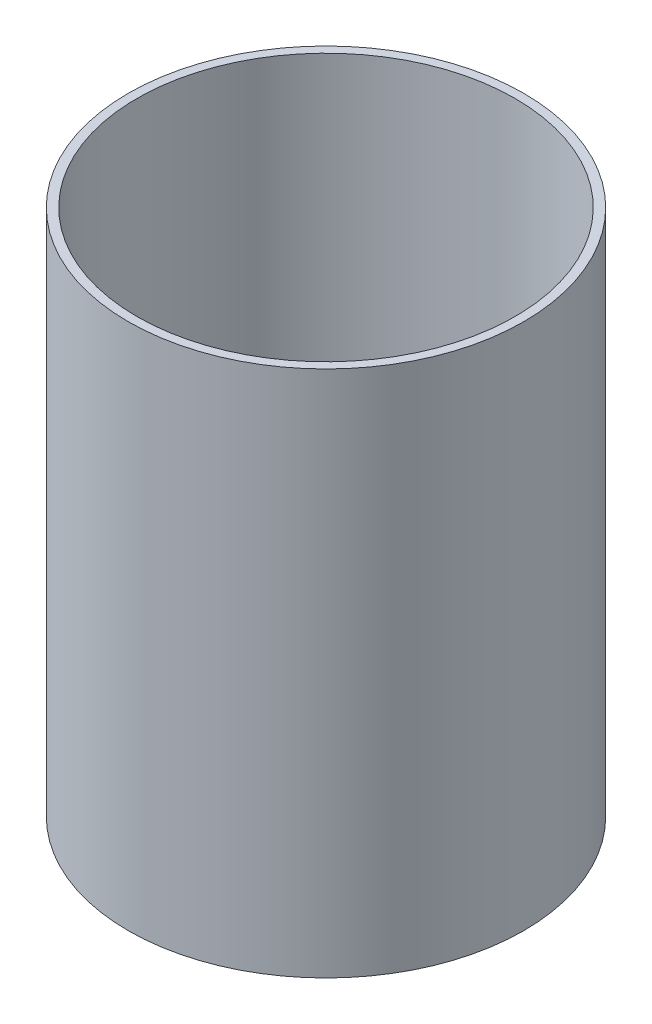
SolidWorks part; units mm, degrees
material "PET"
ref_plane "Front Plane" through (0, 0, 0) normal (0, 0, 1) x (1, 0, 0)
ref_plane "Top Plane" through (0, 0, 0) normal (0, 1, 0) x (1, 0, 0)
ref_plane "Right Plane" through (0, 0, 0) normal (1, 0, 0) x (0, 0, -1)
other "Configuration Table"
sketch "Sketch1" plane through (0, 0, 0) normal (0, 1, 0) x (1, 0, 0)
  circle A0 centre (0, 0) radius 45
  dimension "D1" = 90
extrude "Jar_Body" add sketch "Sketch1" along normal blind 120
sketch "Sketch2" plane through (0, 0, 0) normal (0, 1, 0) x (1, 0, 0)
  circle A0 centre (0, 0) radius 43
  dimension "D1" = 86
extrude "Jar_Inside" cut sketch "Sketch2" against normal blind 117 from offset 120
equation "\"Jar_OD\"= 90  'ASSUMED - Part G fallback - jar outer diameter"
equation "\"Jar_H\"= 120  'ASSUMED - Part G fallback - jar height"
equation "\"Pump_L\"= 45  'ASSUMED - Part G fallback"
equation "\"Pump_W\"= 24  'ASSUMED - Part G fallback"
equation "\"Pump_H\"= 33  'ASSUMED - Part G fallback"
equation "\"Pump_Outlet_OD\"= 7.5  'ASSUMED - Part G fallback"
equation "\"Tube_OD\"= 8  'ASSUMED - Part G fallback"
equation "\"Tube_ID\"= 6  'ASSUMED - Part G fallback"
equation "\"TDS_Body_Dia\"= 12  'ASSUMED - Part G fallback"
equation "\"TDS_Wet_Len\"= 45  'ASSUMED - Part G fallback - length in water"
equation "\"DS_Tube_Dia\"= 6  'ASSUMED - Part G fallback"
equation "\"DS_Tube_Len\"= 50  'ASSUMED - Part G fallback"
equation "\"ORP_Body_Dia\"= 12  'ASSUMED - Part G fallback"
equation "\"ORP_Body_Len\"= 150  'ASSUMED - Part G fallback"
equation "\"ORP_Cap_Dia\"= 16  'ASSUMED - Part G fallback"
equation "\"Turb_W\"= 33  'ASSUMED - Part G fallback - head width"
equation "\"Turb_D\"= 28  'ASSUMED - Part G fallback - head depth"
equation "\"Turb_H\"= 30  'ASSUMED - Part G fallback - head height"
equation "\"Turb_Slot_W\"= 10  'ASSUMED - Part G fallback - slot width"
equation "\"Flow_L\"= 62  'ASSUMED - Part G fallback YF-S201"
equation "\"Flow_W\"= 36  'ASSUMED - Part G fallback"
equation "\"Flow_H\"= 35  'ASSUMED - Part G fallback"
equation "\"Thread_G12_OD\"= 20.955  'ASSUMED - Part G fallback thread G1/2 (major diameter)"
equation "\"Valve_L\"= 75  'ASSUMED - Part G fallback"
equation "\"Valve_W\"= 45  'ASSUMED - Part G fallback"
equation "\"Valve_H\"= 60  'ASSUMED - Part G fallback"
equation "\"Tee_L\"= 40  'ASSUMED - Part G fallback - overall length"
equation "\"Tee_Branch_L\"= 25  'ASSUMED - Part G fallback"
equation "\"Tee_OD\"= 12  'ASSUMED - Part G fallback"
equation "\"Cuv_W\"= 12.5  'ASSUMED - old R3 cuvette (station suppressed in SS4)"
equation "\"Cuv_D\"= 12.5  'ASSUMED - old R3 cuvette (station suppressed in SS4)"
equation "\"Cuv_H\"= 45  'ASSUMED - old R3 cuvette (station suppressed in SS4)"
equation "\"LED_Board_L\"= 20  'ASSUMED - Part G fallback"
equation "\"LED_Board_W\"= 20  'ASSUMED - Part G fallback - LED at centre"
equation "\"GUVA_L\"= 20  'ASSUMED - Part G fallback"
equation "\"GUVA_W\"= 12  'ASSUMED - Part G fallback - sensor at centre"
equation "\"Reed_L\"= 27  'ASSUMED - Part G fallback MC-38 half"
equation "\"Reed_W\"= 14  'ASSUMED - Part G fallback"
equation "\"Reed_H\"= 8  'ASSUMED - Part G fallback"
equation "\"ESP_L\"= 51  'ASSUMED - Part G fallback"
equation "\"ESP_W\"= 28  'ASSUMED - Part G fallback"
equation "\"TFT_L\"= 58  'ASSUMED - Part G fallback - board"
equation "\"TFT_W\"= 35  'ASSUMED - Part G fallback - board"
equation "\"TFT_Win_L\"= 35  'ASSUMED - Part G fallback - visible window"
equation "\"TFT_Win_W\"= 28  'ASSUMED - Part G fallback - visible window"
equation "\"Relay_L\"= 50  'ASSUMED - Part G fallback"
equation "\"Relay_W\"= 26  'ASSUMED - Part G fallback"
equation "\"Relay_H\"= 19  'ASSUMED - Part G fallback"
equation "\"Mosfet_L\"= 34  'ASSUMED - Part G fallback"
equation "\"Mosfet_W\"= 17  'ASSUMED - Part G fallback"
equation "\"Mosfet_H\"= 12  'ASSUMED - Part G fallback"
equation "\"TDS_Board_L\"= 42  'ASSUMED - Part G fallback"
equation "\"TDS_Board_W\"= 32  'ASSUMED - Part G fallback"
equation "\"Turb_Board_L\"= 38  'ASSUMED - Part G fallback"
equation "\"Turb_Board_W\"= 28  'ASSUMED - Part G fallback"
equation "\"BNC_Thread_Dia\"= 9.5  'ASSUMED - Part G fallback"
equation "\"Plate_L\"= 420  'ASSUMED - Part G fallback"
equation "\"Plate_W\"= 297  'ASSUMED - Part G fallback"
equation "\"Plate_T\"= 6  'ASSUMED - Part G fallback"
equation "\"Probe_Clr\"= 0.3  'DESIGN VALUE - Part C rule 3 - printed probe hole = diameter + 0.3"
equation "\"Cuv_Clr\"= 0.2  'DESIGN VALUE - Part C rule 3 - cuvette pocket = size + 0.2"
equation "\"Label_H\"= 0.6  'DESIGN VALUE - Part D - raised label height"
equation "\"D1@Sketch1\" = \"Jar_OD\""
equation "\"D1@Jar_Body\" = \"Jar_H\""
equation "\"Booster_L\"= 150  'ASSUMED - Part G fallback - booster pump"
equation "\"Booster_W\"= 95  'ASSUMED - Part G fallback"
equation "\"Booster_H\"= 100  'ASSUMED - Part G fallback"
equation "\"PTube_OD\"= 6.35  'ASSUMED - Part G fallback - product tube 1/4 inch"
equation "\"Qz_Out\"= 12  'ASSUMED - Part G fallback - quartz channel outside square"
equation "\"Qz_Path\"= 10  'ASSUMED - Part G fallback - quartz channel inside light path"
equation "\"Qz_L\"= 40  'ASSUMED - Part G fallback - quartz channel length"
equation "\"LED860_Dia\"= 5  'ASSUMED - Part G fallback - 860 nm LED"
equation "\"BPW_L\"= 5.4  'ASSUMED - Part G fallback - BPW34"
equation "\"BPW_W\"= 4.3  'ASSUMED - Part G fallback - BPW34"
equation "\"Cart_Dia\"= 50  'ASSUMED - Part G fallback - sediment and pre-carbon cartridges"
equation "\"Cart_L\"= 255  'ASSUMED - Part G fallback"
equation "\"UF_Dia\"= 50  'ASSUMED - Part G fallback - UF cartridge"
equation "\"UF_L\"= 260  'ASSUMED - Part G fallback"
equation "\"RO_Dia\"= 62  'ASSUMED - Part G fallback - RO membrane housing"
equation "\"RO_L\"= 300  'ASSUMED - Part G fallback"
equation "\"UVC_Dia\"= 40  'ASSUMED - Part G fallback - UV-C chamber"
equation "\"UVC_L\"= 300  'ASSUMED - Part G fallback"
equation "\"Tank_W\"= 260  'ASSUMED - Part G fallback - storage tank"
equation "\"Tank_D\"= 160  'ASSUMED - Part G fallback"
equation "\"Tank_H\"= 300  'ASSUMED - Part G fallback"
equation "\"Cab_W\"= 400  'ASSUMED - Part G fallback - purifier cabinet"
equation "\"Cab_D\"= 270  'ASSUMED - Part G fallback"
equation "\"Cab_H\"= 560  'ASSUMED - Part G fallback"
equation "\"ORP_Board_L\"= 40  'ASSUMED - Part G fallback - ORP buffer board"
equation "\"ORP_Board_W\"= 30  'ASSUMED - Part G fallback"
equation "\"Opt_Board_L\"= 50  'ASSUMED - Part G fallback - optical front-end board"
equation "\"Opt_Board_W\"= 40  'ASSUMED - Part G fallback"
equation "\"Buck_L\"= 43  'ASSUMED - Part G fallback - 12 V to 5 V buck module"
equation "\"Buck_W\"= 21  'ASSUMED - Part G fallback"
equation "\"Buck_H\"= 14  'ASSUMED - Part G fallback"
equation "\"BB_L\"= 165  'ASSUMED - Part G fallback - breadboard (As_Built_R3 only)"
equation "\"BB_W\"= 55  'ASSUMED - Part G fallback"
equation "\"BB_H\"= 10  'ASSUMED - Part G fallback"
